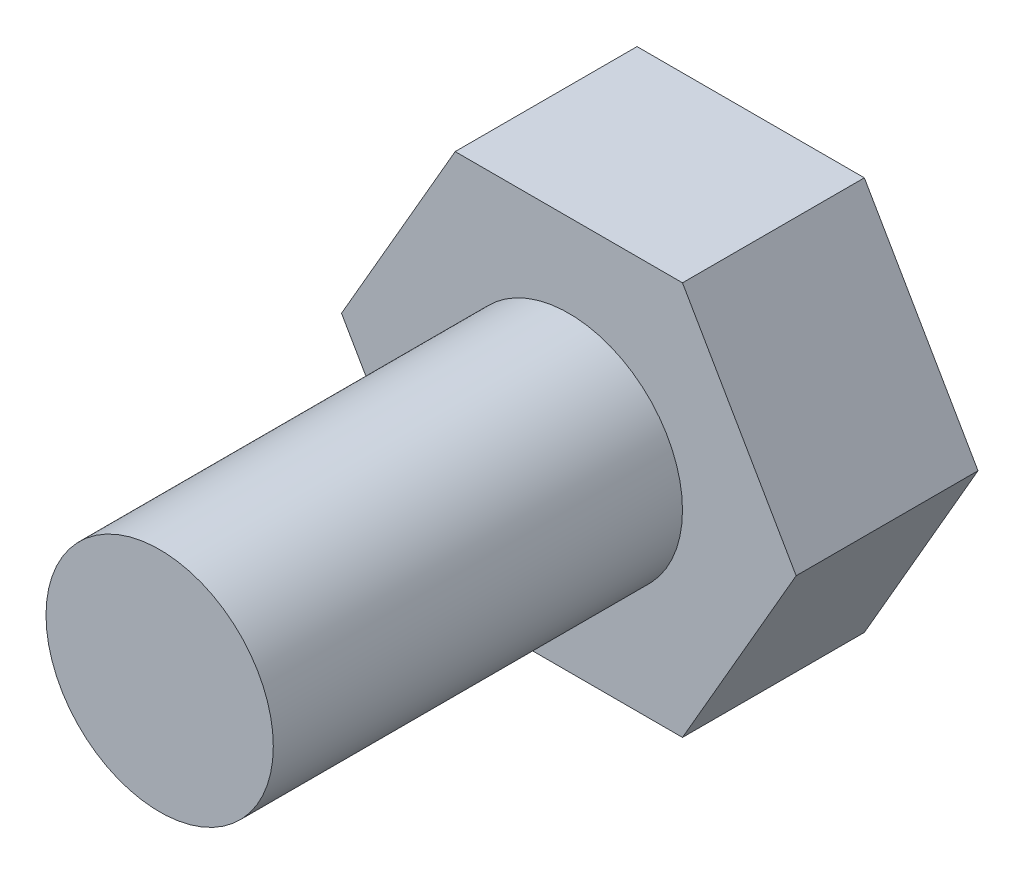
SolidWorks part; units mm, degrees
ref_plane "Front Plane" through (0, 0, 0) normal (0, 0, 1) x (1, 0, 0)
ref_plane "Top Plane" through (0, 0, 0) normal (0, 1, 0) x (1, 0, 0)
ref_plane "Right Plane" through (0, 0, 0) normal (1, 0, 0) x (0, 0, -1)
sketch "Sketch1" plane through (0, 0, 0) normal (0, 0, 1) x (1, 0, 0)
  line L1 (5, 0) -> (2.5, 4.3301)
  line L2 (2.5, 4.3301) -> (-2.5, 4.3301)
  line L3 (-2.5, 4.3301) -> (-5, 0)
  line L4 (-5, 0) -> (-2.5, -4.3301)
  line L5 (-2.5, -4.3301) -> (2.5, -4.3301)
  line L6 (2.5, -4.3301) -> (5, 0)
  circle A0 centre (0, 0) radius 4.3301 construction
  dimension "D1" = 10
extrude "Boss-Extrude1" add sketch "Sketch1" along normal mid plane 4
sketch "Sketch2" plane through (0, 0, 2) normal (0, 0, 1) x (1, 0, 0)
  circle A0 centre (0, 0) radius 2.5
  dimension "D1" = 5
extrude "Boss-Extrude2" add sketch "Sketch2" along normal blind 9
